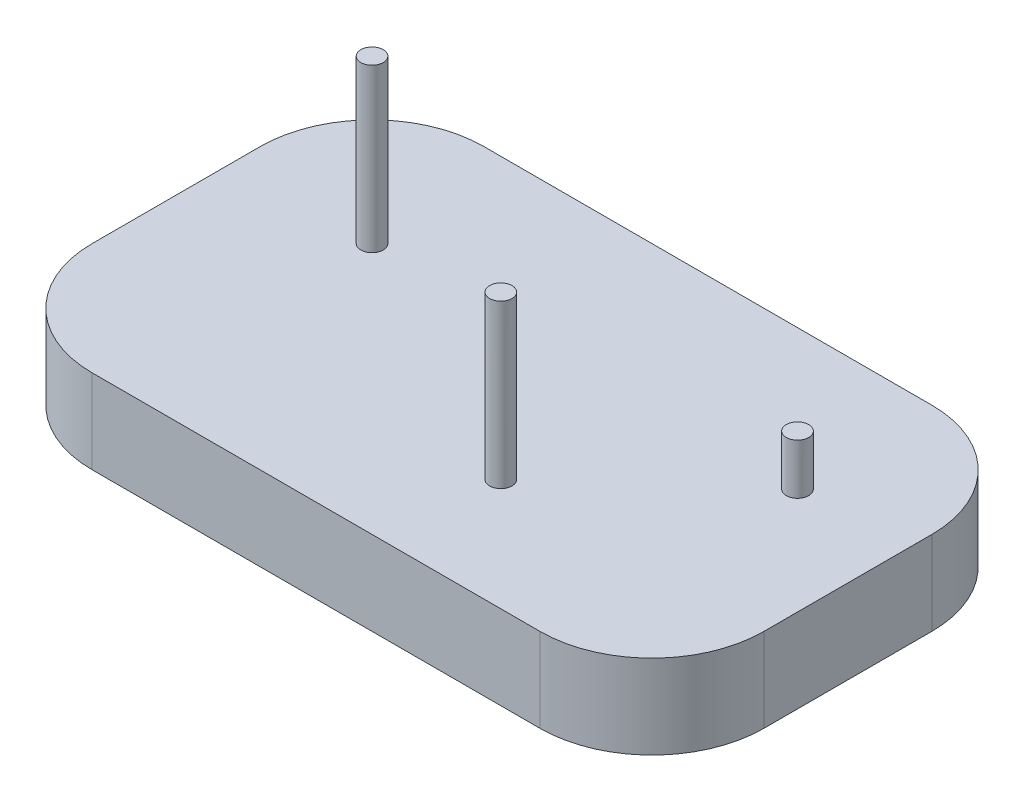
SolidWorks part; units mm, degrees
ref_plane "Front Plane" through (0, 0, 0) normal (0, 0, 1) x (1, 0, 0)
ref_plane "Top Plane" through (0, 0, 0) normal (0, 1, 0) x (1, 0, 0)
ref_plane "Right Plane" through (0, 0, 0) normal (1, 0, 0) x (0, 0, -1)
sketch "Sketch1" plane through (0, 0, 0) normal (0, 1, 0) x (1, 0, 0)
  line L1 (0, 0) -> (120, 0)
  line L2 (0, 0) -> (0, 70)
  line L3 (0, 70) -> (120, 70)
  line L4 (120, 0) -> (120, 70)
  dimension "D1" = 120
  dimension "D2" = 70
extrude "Boss-Extrude1" add sketch "Sketch1" along normal blind 15
fillet "Fillet1" radius 20 4 edges at (120, 7.5, -70) (0, 7.5, -70) (0, 7.5, 0) (120, 7.5, 0)
sketch "Sketch2" plane through (0, 15, 0) normal (0, 1, 0) x (1, 0, 0)
  line L0 (0, 50) -> (0, 20) construction
  line L2 (100, 70) -> (20, 70) construction
  circle A0 centre (25, 45) radius 2
  circle A1 centre (25, 45) radius 35
  circle A2 centre (73, 20) radius 2
  circle A3 centre (73, 20) radius 25
  circle A4 centre (101, 45) radius 2
  circle A5 centre (101, 45) radius 20
  point P13 (0, 0)
  point P14 (0, 0)
  point P15 (0, 0)
  point P16 (0, 0)
  dimension "D1" = 4
  dimension "D2" = 70
  dimension "D3" = 4
  dimension "D4" = 50
  dimension "D8" = 25
  dimension "D10" = 4
  dimension "D11" = 40
  dimension "D5" = 25
  dimension "D6" = 25
  dimension "D7" = 48
  dimension "D9" = 28
  dimension "D12" = 25
extrude "Boss-Extrude3" add sketch "Sketch2" along normal blind 9 contours A0 | A2 | A4 | A1
sketch "Sketch6" plane through (0, 24, 0) normal (0, 1, 0) x (1, 0, 0)
  circle A0 centre (25, 45) radius 2
  circle A1 centre (73, 20) radius 2
  circle A2 centre (25, 45) radius 2 construction
  circle A3 centre (73, 20) radius 2 construction
extrude "Boss-Extrude4" add sketch "Sketch6" along normal blind 20
